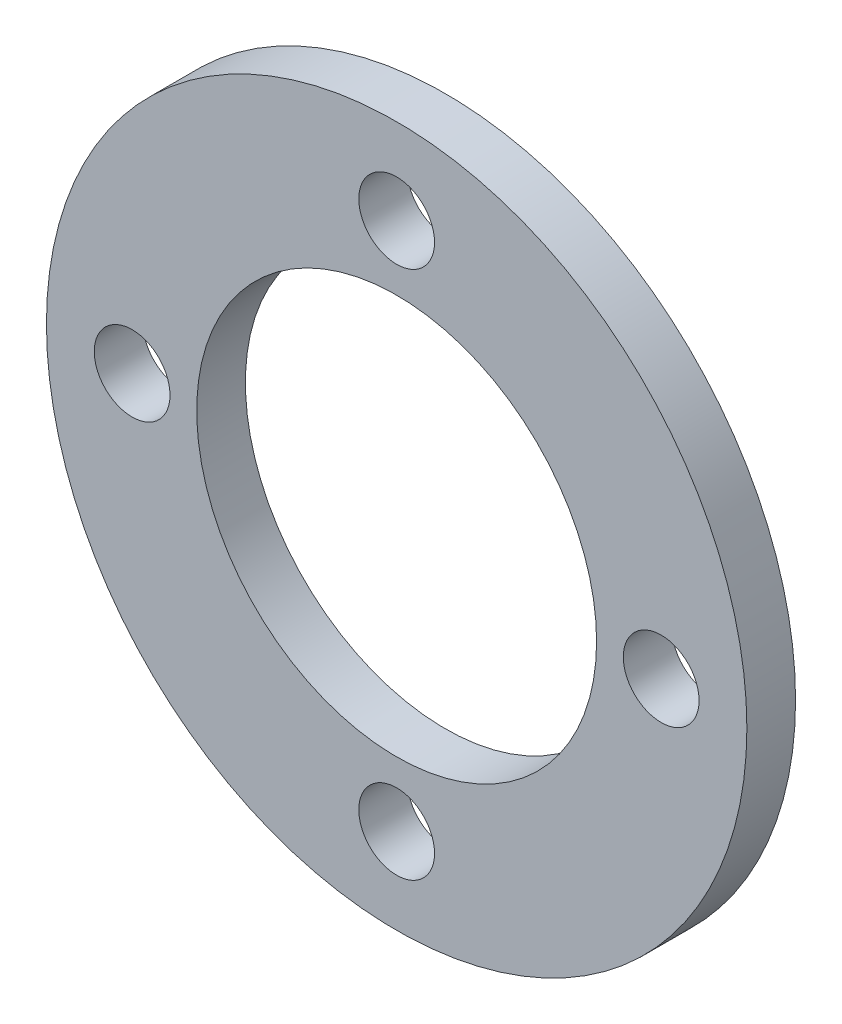
SolidWorks part; units mm, degrees
ref_plane "Piano frontale" through (0, 0, 0) normal (0, 0, 1) x (1, 0, 0)
ref_plane "Piano superiore" through (0, 0, 0) normal (0, 1, 0) x (1, 0, 0)
ref_plane "Piano destro" through (0, 0, 0) normal (1, 0, 0) x (0, 0, -1)
sketch "Schizzo1" plane through (0, 0, 0) normal (0, 0, 1) x (1, 0, 0)
  circle A0 centre (0, 0) radius 10.65 construction
  circle A1 centre (0, 10.65) radius 1.525
  circle A2 centre (10.65, 0) radius 1.525
  circle A3 centre (0, -10.65) radius 1.525
  circle A4 centre (-10.65, 0) radius 1.525
  circle A5 centre (0, 0) radius 8.05
  circle A6 centre (0, 0) radius 14.1
  point P14 (0, 0)
  dimension "D1" = 21.3
  dimension "D2" = 3.05
  dimension "D4" = 28.2
  dimension "D5" = 16.1
  dimension "D3" = 4
extrude "Estrusione-Estrusione1" add sketch "Schizzo1" along normal blind 1.96
